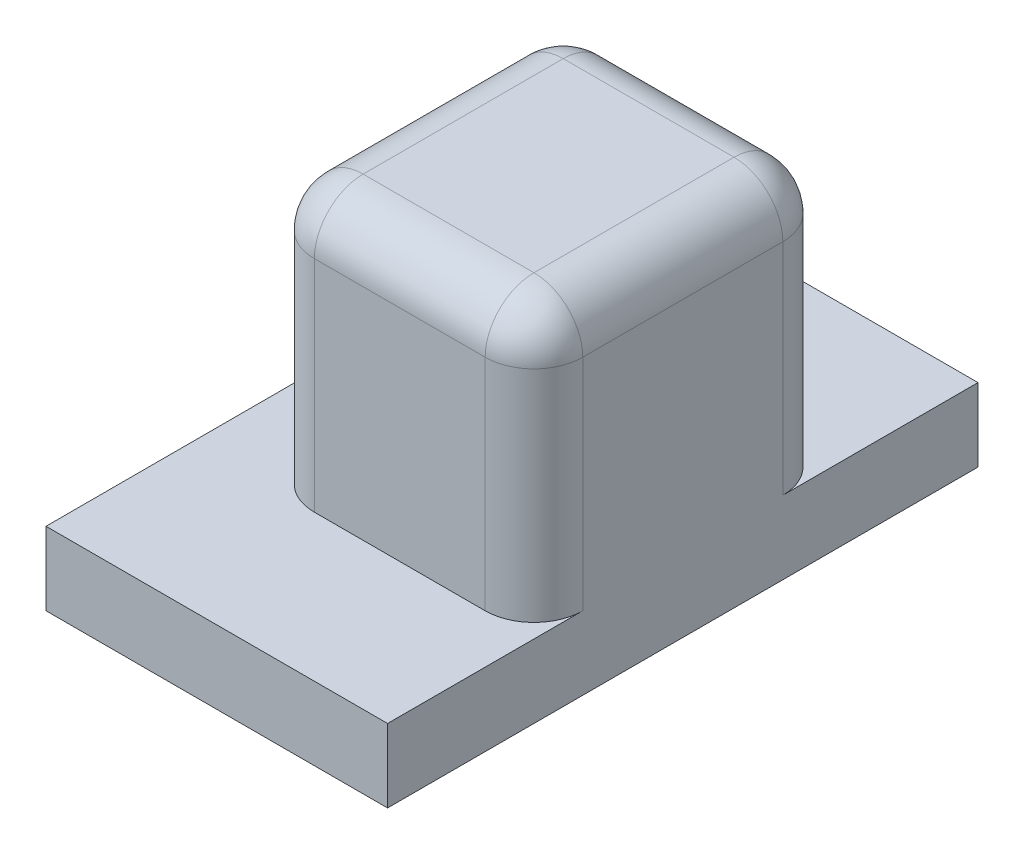
SolidWorks part; units mm, degrees
ref_plane "Front Plane" through (0, 0, 0) normal (0, 0, 1) x (1, 0, 0)
ref_plane "Top Plane" through (0, 0, 0) normal (0, 1, 0) x (1, 0, 0)
ref_plane "Right Plane" through (0, 0, 0) normal (1, 0, 0) x (0, 0, -1)
sketch "Sketch1" plane through (0, 0, 0) normal (0, 1, 0) x (1, 0, 0)
  line L1 (0, 0) -> (5.5, 0)
  line L2 (0, 0) -> (0, 6.1)
  line L3 (0, 6.1) -> (5.5, 6.1)
  line L4 (5.5, 0) -> (5.5, 6.1)
  line L5 (1.2, 1.4) -> (4.5, 1.4)
  line L6 (1.2, 1.4) -> (1.2, 4.7)
  line L7 (1.2, 4.7) -> (4.5, 4.7)
  line L8 (4.5, 1.4) -> (4.5, 4.7)
  dimension "D1" = 3.3
  dimension "D2" = 3.3
  dimension "D3" = 5.5
  dimension "D4" = 1
  dimension "D5" = 1.4
  dimension "D6" = 1.4
extrude "Boss-Extrude1" add sketch "Sketch1" along normal blind 7
sketch "Sketch2" plane through (0, 7, 0) normal (0, 1, 0) x (1, 0, 0)
  line L1 (0, 6.1) -> (5.5, 6.1)
  line L2 (0, 6.1) -> (0, 0)
  line L3 (0, 0) -> (5.5, 0)
  line L4 (5.5, 6.1) -> (5.5, 0)
extrude "Boss-Extrude2" add sketch "Sketch2" against normal blind 1.5
sketch "Sketch3" plane through (0, 0, 0) normal (0, 1, 0) x (1, 0, 0)
  line L0 (5.5, 0) -> (5.5, 6.1) construction
  line L1 (-1.5, 9.1) -> (5.5, 9.1)
  line L2 (-1.5, 9.1) -> (-1.5, -3)
  line L3 (-1.5, -3) -> (5.5, -3)
  line L4 (5.5, 9.1) -> (5.5, -3)
  line L5 (5.5, 6.1) -> (0, 6.1) construction
  line L6 (0, 0) -> (5.5, 0) construction
  line L7 (0, 6.1) -> (0, 0) construction
  line L9 (4.5, 4.7) -> (1.2, 4.7)
  line L10 (4.5, 4.7) -> (4.5, 1.4)
  line L11 (4.5, 1.4) -> (1.2, 1.4)
  line L12 (1.2, 4.7) -> (1.2, 1.4)
  dimension "D1" = 3
  dimension "D2" = 3
  dimension "D3" = 1.5
extrude "Boss-Extrude3" add sketch "Sketch3" along normal blind 1.5
fillet "Fillet1" radius 1 8 edges at (0, 4.25, -6.1) (0, 4.25, 0) (5.5, 4.25, 0) (5.5, 4.25, -6.1) (5.5, 7, -3.05) (0, 7, -3.05) (2.75, 7, -6.1) (2.75, 7, 0)
